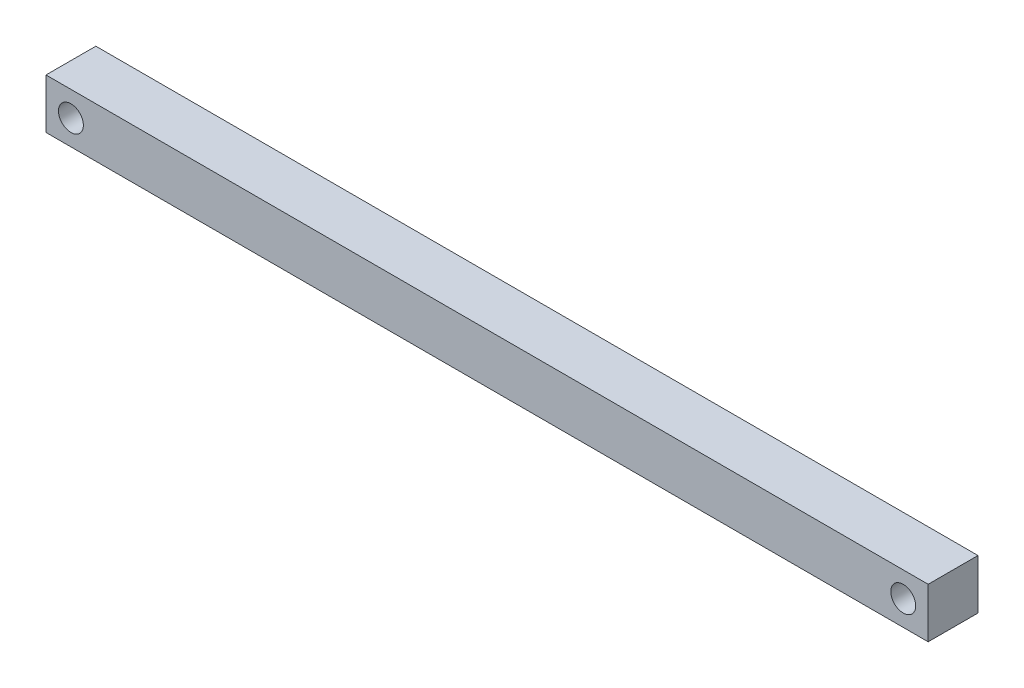
SolidWorks part; units mm, degrees
ref_plane "Front Plane" through (0, 0, 0) normal (0, 0, 1) x (1, 0, 0)
ref_plane "Top Plane" through (0, 0, 0) normal (0, 1, 0) x (1, 0, 0)
ref_plane "Right Plane" through (0, 0, 0) normal (1, 0, 0) x (0, 0, -1)
sketch "Sketch1" plane through (0, 0, 0) normal (0, 0, 1) x (1, 0, 0)
  line L0 (250.5, 0) -> (-250.5, 0) construction
  line L1 (265.5, 15) -> (-265.5, 15)
  line L2 (265.5, 15) -> (265.5, -15)
  line L3 (265.5, -15) -> (-265.5, -15)
  line L4 (-265.5, 15) -> (-265.5, -15)
  line L5 (265.5, 15) -> (-265.5, -15) construction
  line L6 (265.5, -15) -> (-265.5, 15) construction
  circle A0 centre (-250.5, 0) radius 7.5
  circle A1 centre (250.5, 0) radius 7.5
  point P0 (0, 0)
  point P8 (0, 0)
  dimension "D2" = 15
  dimension "D1" = 30
  dimension "D3" = 501
  dimension "D4" = 15
extrude "Boss-Extrude1" add sketch "Sketch1" along normal mid plane 30
equation "\"A\"= 200"
equation "\"hole_diameter\"=15"
equation "\"D2@Sketch1\"=\"hole_diameter\""
equation "\"r5\"=501"
equation "\"D3@Sketch1\"=\"r5\""
equation "\"D4@Sketch1\"=\"hole_diameter\""
equation "\"r15\"=499"
